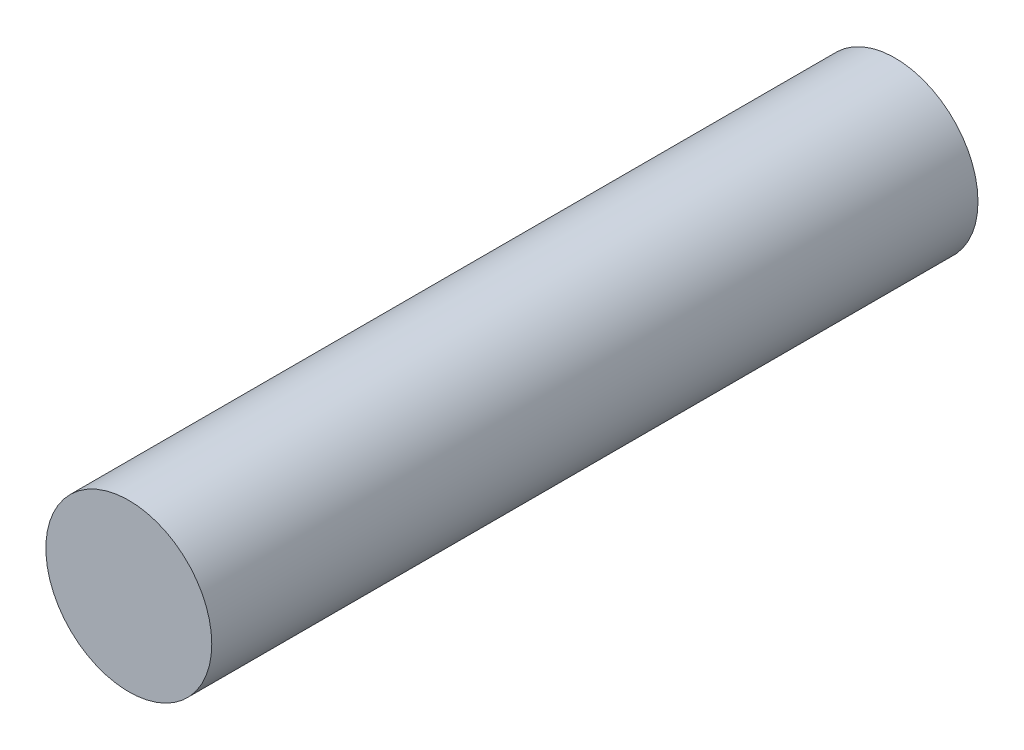
SolidWorks part; units mm, degrees
ref_plane "前视基准面" through (0, 0, 0) normal (0, 0, 1) x (1, 0, 0)
ref_plane "上视基准面" through (0, 0, 0) normal (0, 1, 0) x (1, 0, 0)
ref_plane "右视基准面" through (0, 0, 0) normal (1, 0, 0) x (0, 0, -1)
other "Configuration Table"
sketch "草图1" plane through (0, 0, 0) normal (0, 0, 1) x (1, 0, 0)
  circle A0 centre (0, 0) radius 2
  dimension "diameter" = 4
extrude "Cable_envelope" add sketch "草图1" along normal blind 18.47
